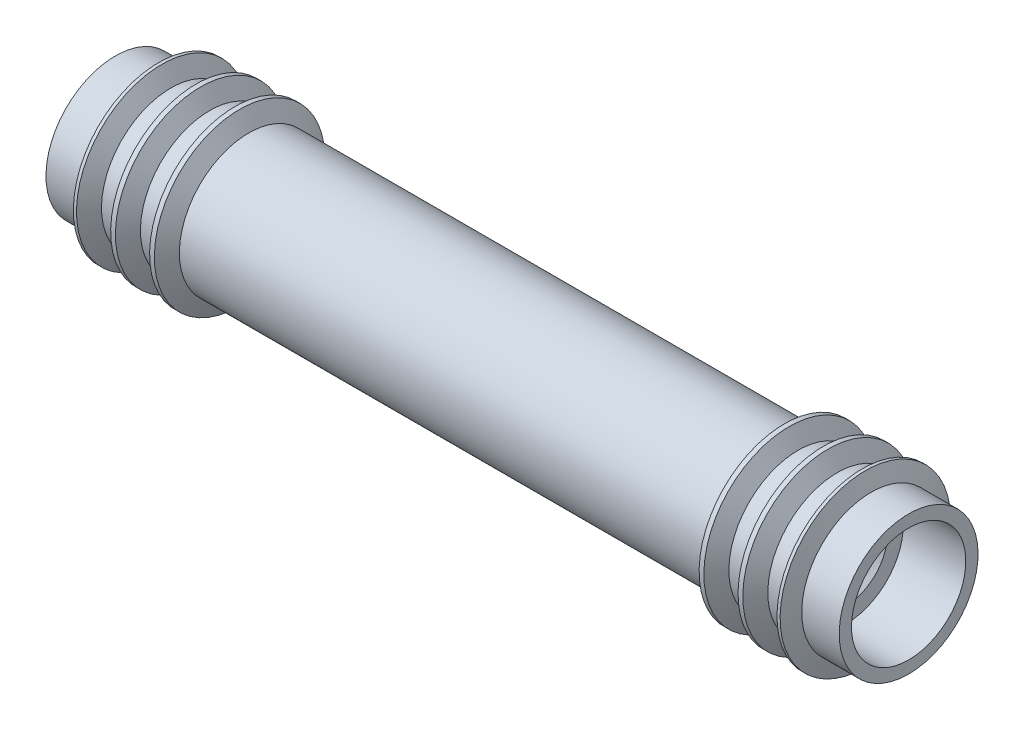
SolidWorks part; units mm, degrees
ref_plane "Front Plane" through (0, 0, 0) normal (0, 0, 1) x (1, 0, 0)
ref_plane "Top Plane" through (0, 0, 0) normal (0, 1, 0) x (1, 0, 0)
ref_plane "Right Plane" through (0, 0, 0) normal (1, 0, 0) x (0, 0, -1)
sketch "Sketch2" plane through (0, 0, 0) normal (0, 0, 1) x (1, 0, 0)
  line L0 (0, 0) -> (0, 28.4375) construction
  line L1 (-31.75, 4.575) -> (-26.75, 4.575) construction
  line L2 (-31.75, 4.575) -> (-31.75, -4.575) construction
  line L3 (-31.75, -4.575) -> (-26.75, -4.575) construction
  line L4 (-26.75, 4.575) -> (-26.75, -4.575) construction
  line L5 (-31.75, 4.575) -> (-26.75, -4.575) construction
  line L6 (-31.75, -4.575) -> (-26.75, 4.575) construction
  line L7 (26.75, 4.5) -> (36.8332, 4.5) construction
  line L8 (26.75, 4.5) -> (26.75, -4.5) construction
  line L9 (26.75, -4.5) -> (36.8332, -4.5) construction
  line L10 (36.8332, 4.5) -> (36.8332, -4.5) construction
  line L11 (26.75, 4.5) -> (36.8332, -4.5) construction
  line L12 (26.75, -4.5) -> (36.8332, 4.5) construction
  line L13 (-31.75, 0) -> (36.8332, 0) construction
  line L14 (-31.75, 5.5562) -> (-28.75, 5.5562)
  line L15 (-28.75, 5.5562) -> (-28.2878, 6.8262)
  line L16 (-28.2878, 6.8262) -> (-28.0382, 6.8262)
  line L19 (-25.3018, 6.8262) -> (-24.9208, 6.8262)
  line L20 (-24.9208, 6.8262) -> (-24.1875, 5.5562)
  line L21 (-19.6952, 3.175) -> (0, 3.175) construction
  line L22 (-31.75, 5.5562) -> (-31.75, 4.575)
  line L23 (-31.75, 4.575) -> (-26.75, 4.575)
  line L24 (-26.75, 4.575) -> (-26.75, 0)
  line L25 (-26.75, 0) -> (0, 0)
  line L26 (0, 0) -> (0, 3.175)
  line L27 (-33.2419, -5.5563) -> (-33.2419, 5.5562) construction
  line L28 (-26.67, 5.5562) -> (-26.67, 7.68) construction
  line L29 (-26.67, 5.5562) -> (26.67, 5.5562) construction
  line L30 (-31.75, 5.5562) -> (31.75, 5.5562) construction
  line L31 (0, 1.6) -> (-12.5, 1.6) construction
  line L32 (-12.5, 1.6) -> (-14.1, 0) construction
  line L33 (-12.5, 1.6) -> (-12.5, -1.6) construction
  line L34 (-12.5, 1.6) -> (12.5, 1.6) construction
  line L35 (-26.75, 1.7145) -> (-21.925, 1.7145)
  line L36 (-21.925, 1.7145) -> (-21.925, 0)
  line L37 (-26.75, 3.305) -> (-26.242, 2.797)
  line L38 (-21.925, 1.7145) -> (-34.925, 1.7145) construction
  line L39 (-21.925, 1.7145) -> (-21.925, -1.7145) construction
  line L40 (-21.925, -1.7145) -> (-34.925, -1.7145) construction
  line L41 (-34.925, 1.7145) -> (-34.925, -1.7145) construction
  line L42 (-26.242, 2.797) -> (-26.242, 0)
  line L43 (-27.305, 5.5562) -> (-26.035, 5.5562)
  line L44 (-28.0382, 6.8262) -> (-27.305, 5.5562)
  line L45 (-25.3018, 6.8262) -> (-26.035, 5.5562)
  line L46 (-24.1875, 5.5562) -> (-22.9175, 5.5562)
  line L47 (-22.9175, 5.5562) -> (-22.1843, 6.8262)
  line L48 (-22.1843, 6.8262) -> (-21.8033, 6.8262)
  line L49 (-21.8033, 6.8262) -> (-21.0701, 5.5562)
  line L50 (-24.1875, 5.5562) -> (-22.8127, 3.175) construction
  line L51 (-23.5525, 5.5562) -> (-23.5525, 7.9749) construction
  line L52 (-22.8127, 3.175) -> (-19.6952, 3.175) construction
  line L53 (-21.0701, 5.5562) -> (0, 5.5562)
  line L54 (0, 5.5562) -> (0, 3.175)
  line L55 (-21.0701, 5.5562) -> (-19.6952, 3.175) construction
  point P0 (-29.25, 0)
  point P5 (31.7916, 0)
  point P27 (-33.2419, 0)
  point P29 (-12.5, 0)
  point P33 (0, 5.5562)
  point P36 (0, 1.6)
  point P48 (-21.925, 0)
  point P51 (0, 5.5562)
  point P53 (-26.67, 5.5562)
  dimension "D1" = 5
  dimension "D4" = 11.1125
  dimension "D5" = 9.15
  dimension "D6" = 60
  dimension "D7" = 60
  dimension "D8" = 1.27
  dimension "D9" = 70
  dimension "D10" = 53.34
  dimension "D11" = 63.5
  dimension "D12" = 0.381
  dimension "D13" = 45
  dimension "D14" = 25
  dimension "D16" = 3.429
  dimension "D17" = 3.175
  dimension "D18" = 1.27
  dimension "D19" = 0.508
  dimension "D20" = 45
  dimension "D21" = 13
  dimension "D22" = 3
  dimension "D23" = 1.27
  dimension "D24" = 0.381
revolve "Revolve1" add sketch "Sketch2" angle 360 about L13
mirror "Mirror1" about plane through (0, 0, 0) normal (1, 0, 0) of bodies 101
chamfer "Chamfer1" distance 0.508 angle 45 1 edges at (-31.75, -4.575, 0)
